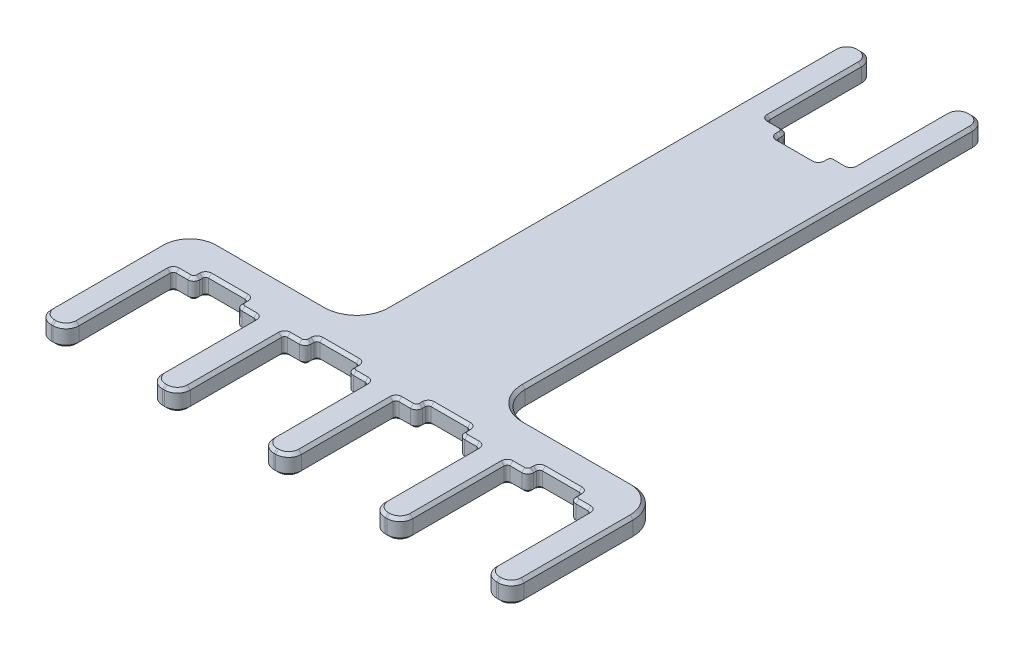
SolidWorks part; units mm, degrees
ref_plane "Front Plane" through (0, 0, 0) normal (0, 0, 1) x (1, 0, 0)
ref_plane "Top Plane" through (0, 0, 0) normal (0, 1, 0) x (1, 0, 0)
ref_plane "Right Plane" through (0, 0, 0) normal (1, 0, 0) x (0, 0, -1)
sketch "Sketch2" plane through (0, 0, 0) normal (0, 1, 0) x (1, 0, 0)
  line L0 (-5.3917, -1.575) -> (8.8083, -1.575)
  line L1 (-24.2917, -1.575) -> (-10.0917, -1.575)
  line L2 (-24.2917, -1.575) -> (-24.2917, -15.775)
  line L3 (-24.2917, -15.775) -> (-10.0917, -15.775)
  line L4 (-10.0917, -1.575) -> (-10.0917, -15.775)
  line L17 (-5.3917, -1.575) -> (-5.3917, -15.775)
  line L18 (-5.3917, -15.775) -> (8.8083, -15.775)
  line L19 (8.8083, -1.575) -> (8.8083, -15.775)
  line L20 (13.5083, -1.575) -> (27.7083, -1.575)
  line L21 (13.5083, -1.575) -> (13.5083, -15.775)
  line L22 (13.5083, -15.775) -> (27.7083, -15.775)
  line L23 (27.7083, -1.575) -> (27.7083, -15.775)
  line L24 (32.4083, -1.575) -> (46.6083, -1.575)
  line L25 (32.4083, -1.575) -> (32.4083, -15.775)
  line L26 (32.4083, -15.775) -> (46.6083, -15.775)
  line L27 (46.6083, -1.575) -> (46.6083, -15.775)
  line L28 (1.7083, -1.575) -> (1.7083, -15.775) construction
  line L29 (-17.1917, -15.775) -> (-17.1917, -1.575) construction
  dimension "D1" = 14.2
  dimension "D3" = 18.9
  dimension "D2" = 4
sketch "Sketch1" plane through (0, 0, 0) normal (0, 1, 0) x (1, 0, 0)
  line L0 (-28.9917, 5.925) -> (-0.6417, 5.925)
  line L1 (-0.6417, 5.925) -> (-0.6417, 89.125)
  line L3 (22.9583, 89.125) -> (22.9583, 5.925)
  line L4 (22.9583, 5.925) -> (51.3083, 5.925)
  line L5 (51.3083, 5.925) -> (51.3083, -19.775)
  line L6 (51.3083, -19.775) -> (-28.9917, -19.775)
  line L7 (-28.9917, -19.775) -> (-28.9917, 5.925)
  line L8 (-5.3917, -8.675) -> (-10.0917, -8.675) construction
  line L9 (-5.3917, -1.575) -> (-5.3917, -15.775) construction
  line L10 (-10.0917, -1.575) -> (-10.0917, -15.775) construction
  line L11 (46.6083, -8.675) -> (51.3083, -8.675) construction
  line L12 (46.6083, -1.575) -> (46.6083, -15.775) construction
  line L13 (-24.2917, -8.675) -> (-28.9917, -8.675) construction
  line L14 (-24.2917, -1.575) -> (-24.2917, -15.775) construction
  line L15 (18.2583, 70.925) -> (22.9583, 70.925) construction
  line L17 (-17.1917, -1.575) -> (-17.1917, -19.775) construction
  line L19 (-24.2917, -15.775) -> (-10.0917, -15.775) construction
  line L20 (-24.2917, -1.575) -> (-10.0917, -1.575) construction
  line L21 (4.0583, 89.125) -> (4.0583, 70.925)
  line L22 (4.0583, 70.925) -> (18.2583, 70.925)
  line L23 (18.2583, 70.925) -> (18.2583, 89.125)
  line L24 (-0.6417, 89.125) -> (4.0583, 89.125)
  line L25 (18.2583, 89.125) -> (22.9583, 89.125)
  line L26 (13.5083, -1.575) -> (27.7083, -1.575) construction
  line L27 (8.8083, -8.675) -> (13.5083, -8.675) construction
  line L28 (8.8083, -1.575) -> (8.8083, -15.775) construction
  line L29 (13.5083, -1.575) -> (13.5083, -15.775) construction
  line L30 (11.1583, 70.925) -> (11.1583, 89.125) construction
  line L31 (11.1583, -8.675) -> (11.1583, 70.925) construction
  line L32 (4.0583, 89.125) -> (18.2583, 89.125) construction
  dimension "D1" = 4
  dimension "D2" = 7.5
  dimension "D3" = 65
extrude "Boss-Extrude1" add sketch "Sketch1" along normal blind 3.4
sketch "Sketch3" plane through (0, 3.4, 0) normal (0, 1, 0) x (1, 0, 0)
  line L0 (-28.9917, -19.775) -> (51.3083, -19.775) construction
  line L2 (-24.2917, -1.575) -> (-24.2917, -19.775)
  line L3 (-24.2917, -19.775) -> (-10.0917, -19.775)
  line L4 (-10.0917, -1.575) -> (-10.0917, -19.775)
  line L5 (32.4083, -15.775) -> (46.6083, -15.775) construction
  line L7 (-5.3917, -1.575) -> (-5.3917, -19.775)
  line L8 (-5.3917, -19.775) -> (8.8083, -19.775)
  line L9 (8.8083, -1.575) -> (8.8083, -19.775)
  line L11 (13.5083, -1.575) -> (13.5083, -19.775)
  line L12 (13.5083, -19.775) -> (27.7083, -19.775)
  line L13 (27.7083, -1.575) -> (27.7083, -19.775)
  line L15 (32.4083, -1.575) -> (32.4083, -19.775)
  line L16 (32.4083, -19.775) -> (46.6083, -19.775)
  line L17 (46.6083, -1.575) -> (46.6083, -19.775)
  line L18 (-24.2917, -1.575) -> (-20.7917, -1.575)
  line L19 (-20.7917, -1.575) -> (-20.7917, 0.425)
  line L20 (-20.7917, 0.425) -> (-13.5917, 0.425)
  line L21 (-13.5917, 0.425) -> (-13.5917, -1.575)
  line L22 (-13.5917, -1.575) -> (-10.0917, -1.575)
  line L23 (-5.3917, -1.575) -> (-1.8917, -1.575)
  line L24 (-1.8917, -1.575) -> (-1.8917, 0.425)
  line L25 (-1.8917, 0.425) -> (5.3083, 0.425)
  line L26 (5.3083, 0.425) -> (5.3083, -1.575)
  line L27 (5.3083, -1.575) -> (8.8083, -1.575)
  line L28 (13.5083, -1.575) -> (17.0083, -1.575)
  line L29 (17.0083, -1.575) -> (17.0083, 0.425)
  line L30 (17.0083, 0.425) -> (24.2083, 0.425)
  line L31 (24.2083, 0.425) -> (24.2083, -1.575)
  line L32 (24.2083, -1.575) -> (27.7083, -1.575)
  line L33 (32.4083, -1.575) -> (35.9083, -1.575)
  line L34 (35.9083, -1.575) -> (35.9083, 0.425)
  line L35 (35.9083, 0.425) -> (43.1083, 0.425)
  line L36 (43.1083, 0.425) -> (43.1083, -1.575)
  line L37 (43.1083, -1.575) -> (46.6083, -1.575)
  line L38 (7.5583, 70.925) -> (7.5583, 68.925)
  line L39 (18.2583, 70.925) -> (4.0583, 70.925) construction
  line L40 (7.5583, 68.925) -> (14.7583, 68.925)
  line L41 (14.7583, 68.925) -> (14.7583, 70.925)
  line L42 (7.5583, 70.925) -> (14.7583, 70.925)
  line L43 (4.0583, 70.925) -> (7.5583, 70.925) construction
  line L44 (14.7583, 70.925) -> (18.2583, 70.925) construction
  dimension "D1" = 3.5
  dimension "D2" = 2
extrude "Cut-Extrude1" cut sketch "Sketch3" against normal blind 3.4
fillet "Fillet1" radius 5 4 edges at (-28.9917, 1.7, -5.925) (51.3083, 1.7, -5.925) (22.9583, 1.7, -5.925) (-0.6417, 1.7, -5.925)
fillet "Fillet2" radius 2.2 14 edges at (-0.6417, 1.7, -89.125) (4.0583, 1.7, -89.125) (18.2583, 1.7, -89.125) (22.9583, 1.7, -89.125) (51.3083, 1.7, 19.775) (46.6083, 1.7, 19.775) (32.4083, 1.7, 19.775) (27.7083, 1.7, 19.775) (13.5083, 1.7, 19.775) (8.8083, 1.7, 19.775) (-5.3917, 1.7, 19.775) (-10.0917, 1.7, 19.775) (-24.2917, 1.7, 19.775) (-28.9917, 1.7, 19.775)
fillet "Fillet3" radius 0.5 20 edges at (17.0083, 1.7, -0.425) (-1.8917, 1.7, -0.425) (-20.7917, 1.7, -0.425) (-13.5917, 1.7, -0.425) (5.3083, 1.7, -0.425) (24.2083, 1.7, -0.425) (35.9083, 1.7, -0.425) (43.1083, 1.7, -0.425) (46.6083, 1.7, 1.575) (32.4083, 1.7, 1.575) (13.5083, 1.7, 1.575) (27.7083, 1.7, 1.575) (8.8083, 1.7, 1.575) (-5.3917, 1.7, 1.575) (-10.0917, 1.7, 1.575) (-24.2917, 1.7, 1.575) (7.5583, 1.7, -68.925) (14.7583, 1.7, -68.925) (18.2583, 1.7, -70.925) (4.0583, 1.7, -70.925)
fillet "Fillet4" radius 1 10 edges at (-13.5917, 1.7, 1.575) (-1.8917, 1.7, 1.575) (5.3083, 1.7, 1.575) (17.0083, 1.7, 1.575) (24.2083, 1.7, 1.575) (35.9083, 1.7, 1.575) (43.1083, 1.7, 1.575) (-20.7917, 1.7, 1.575) (14.7583, 1.7, -70.925) (7.5583, 1.7, -70.925)
chamfer "Chamfer1" distance 0.5 192 edges at (-1.8917, 0, 0.325) (-1.7452, 0, -0.2786) (-2.1846, 0, 1.2821) (1.7083, 0, -0.425) (-3.8917, 0, 1.575) (5.1619, 0, -0.2786) (-5.2452, 0, 1.7214) (5.3083, 0, 0.325) (-5.3917, 0, 9.825) (5.6012, 0, 1.2821) (-6.036, 0, 19.1306) (7.3083, 0, 1.575) (-7.7417, 0, 19.775) (8.6619, 0, 1.7214) (-9.4473, 0, 19.1306) (8.8083, 0, 9.825) (-10.0917, 0, 9.825) (9.4527, 0, 19.1306) (-10.2381, 0, 1.7214) (11.1583, 0, 19.775) (-11.5917, 0, 1.575) (12.864, 0, 19.1306) (-13.2988, 0, 1.2821) (13.5083, 0, 9.825) (-13.5917, 0, 0.325) (13.6548, 0, 1.7214) (-13.7381, 0, -0.2786) (15.0083, 0, 1.575) (-17.1917, 0, -0.425) (16.7154, 0, 1.2821) (-20.6452, 0, -0.2786) (17.0083, 0, 0.325) (-20.7917, 0, 0.325) (17.1548, 0, -0.2786) (-21.0846, 0, 1.2821) (20.6083, 0, -0.425) (-22.7917, 0, 1.575) (24.0619, 0, -0.2786) (-24.1452, 0, 1.7214) (24.2083, 0, 0.325) (-24.2917, 0, 9.825) (24.5012, 0, 1.2821) (-24.936, 0, 19.1306) (26.2083, 0, 1.575) (-26.6417, 0, 19.775) (27.5619, 0, 1.7214) (-28.3473, 0, 19.1306) (27.7083, 0, 9.825) (-28.9917, 0, 8.325) (28.3527, 0, 19.1306) (-27.5272, 0, -4.4605) (30.0583, 0, 19.775) (-14.8167, 0, -5.925) (31.764, 0, 19.1306) (-2.1061, 0, -7.3895) (32.4083, 0, 9.825) (-0.6417, 0, -48.925) (32.5548, 0, 1.7214) (0.0027, 0, -88.4806) (33.9083, 0, 1.575) (1.7083, 0, -89.125) (35.6154, 0, 1.2821) (3.414, 0, -88.4806) (35.9083, 0, 0.325) (4.0583, 0, -79.175) (36.0548, 0, -0.2786) (4.2048, 0, -71.0714) (39.5083, 0, -0.425) (5.5583, 0, -70.925) (42.9619, 0, -0.2786) (7.2654, 0, -70.6321) (43.1083, 0, 0.325) (7.5583, 0, -69.675) (43.4012, 0, 1.2821) (7.7048, 0, -69.0714) (45.1083, 0, 1.575) (11.1583, 0, -68.925) (46.4619, 0, 1.7214) (14.6119, 0, -69.0714) (46.6083, 0, 9.825) (14.7583, 0, -69.675) (47.2527, 0, 19.1306) (15.0512, 0, -70.6321) (48.9583, 0, 19.775) (16.7583, 0, -70.925) (50.664, 0, 19.1306) (18.1119, 0, -71.0714) (51.3083, 0, 8.325) (18.2583, 0, -79.175) (49.8439, 0, -4.4605) (18.9027, 0, -88.4806) (37.1333, 0, -5.925) (20.6083, 0, -89.125) (24.4228, 0, -7.3895) (22.314, 0, -88.4806) (22.9583, 0, -48.925) (-1.8917, 3.4, 0.325) (-1.7452, 3.4, -0.2786) (-2.1846, 3.4, 1.2821) (1.7083, 3.4, -0.425) (-3.8917, 3.4, 1.575) (5.1619, 3.4, -0.2786) (-5.2452, 3.4, 1.7214) (5.3083, 3.4, 0.325) (-5.3917, 3.4, 9.825) (5.6012, 3.4, 1.2821) (-6.036, 3.4, 19.1306) (7.3083, 3.4, 1.575) (-7.7417, 3.4, 19.775) (8.6619, 3.4, 1.7214) (-9.4473, 3.4, 19.1306) (8.8083, 3.4, 9.825) (-10.0917, 3.4, 9.825) (9.4527, 3.4, 19.1306) (-10.2381, 3.4, 1.7214) (11.1583, 3.4, 19.775) (-11.5917, 3.4, 1.575) (12.864, 3.4, 19.1306) (-13.2988, 3.4, 1.2821) (13.5083, 3.4, 9.825) (-13.5917, 3.4, 0.325) (13.6548, 3.4, 1.7214) (-13.7381, 3.4, -0.2786) (15.0083, 3.4, 1.575) (-17.1917, 3.4, -0.425) (16.7154, 3.4, 1.2821) (-20.6452, 3.4, -0.2786) (17.0083, 3.4, 0.325) (-20.7917, 3.4, 0.325) (17.1548, 3.4, -0.2786) (-21.0846, 3.4, 1.2821) (20.6083, 3.4, -0.425) (-22.7917, 3.4, 1.575) (24.0619, 3.4, -0.2786) (-24.1452, 3.4, 1.7214) (24.2083, 3.4, 0.325) (-24.2917, 3.4, 9.825) (24.5012, 3.4, 1.2821) (-24.936, 3.4, 19.1306) (26.2083, 3.4, 1.575) (-26.6417, 3.4, 19.775) (27.5619, 3.4, 1.7214) (-28.3473, 3.4, 19.1306) (27.7083, 3.4, 9.825) (-28.9917, 3.4, 8.325) (28.3527, 3.4, 19.1306) (-27.5272, 3.4, -4.4605) (30.0583, 3.4, 19.775) (-14.8167, 3.4, -5.925) (31.764, 3.4, 19.1306) (-2.1061, 3.4, -7.3895) (32.4083, 3.4, 9.825) (-0.6417, 3.4, -48.925) (32.5548, 3.4, 1.7214) (0.0027, 3.4, -88.4806) (33.9083, 3.4, 1.575) (1.7083, 3.4, -89.125) (35.6154, 3.4, 1.2821) (3.414, 3.4, -88.4806) (35.9083, 3.4, 0.325) (4.0583, 3.4, -79.175) (36.0548, 3.4, -0.2786) (4.2048, 3.4, -71.0714) (39.5083, 3.4, -0.425) (5.5583, 3.4, -70.925) (42.9619, 3.4, -0.2786) (7.2654, 3.4, -70.6321) (43.1083, 3.4, 0.325) (7.5583, 3.4, -69.675) (43.4012, 3.4, 1.2821) (7.7048, 3.4, -69.0714) (45.1083, 3.4, 1.575) (11.1583, 3.4, -68.925) (46.4619, 3.4, 1.7214) (14.6119, 3.4, -69.0714) (46.6083, 3.4, 9.825) (14.7583, 3.4, -69.675) (47.2527, 3.4, 19.1306) (15.0512, 3.4, -70.6321) (48.9583, 3.4, 19.775) (16.7583, 3.4, -70.925) (50.664, 3.4, 19.1306) (18.1119, 3.4, -71.0714) (51.3083, 3.4, 8.325) (18.2583, 3.4, -79.175) (49.8439, 3.4, -4.4605) (18.9027, 3.4, -88.4806) (37.1333, 3.4, -5.925) (20.6083, 3.4, -89.125) (24.4228, 3.4, -7.3895) (22.314, 3.4, -88.4806) (22.9583, 3.4, -48.925)
